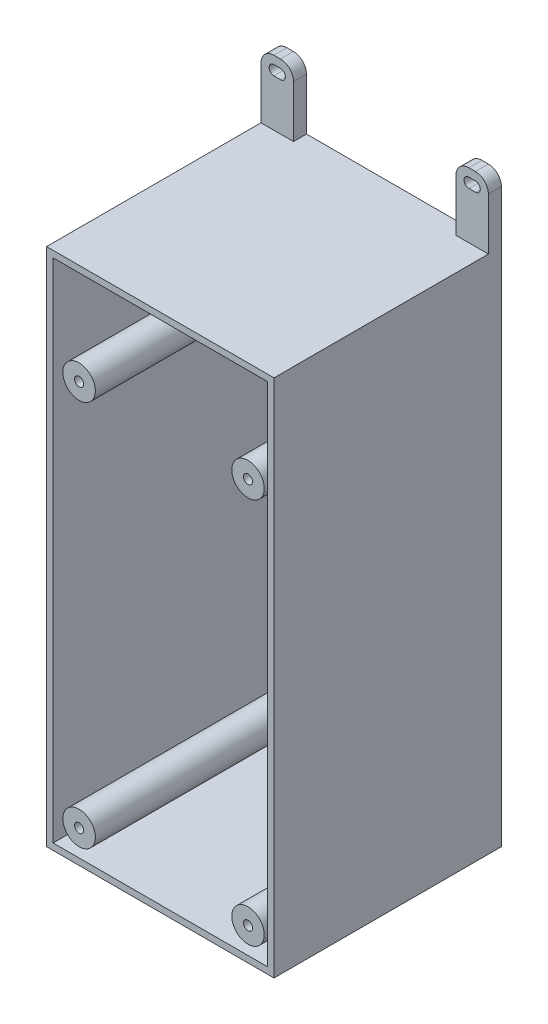
SolidWorks part; units mm, degrees
material "ABS"
ref_plane "Alzado" through (0, 0, 0) normal (0, 0, 1) x (1, 0, 0)
ref_plane "Planta" through (0, 0, 0) normal (0, 1, 0) x (1, 0, 0)
ref_plane "Vista lateral" through (0, 0, 0) normal (1, 0, 0) x (0, 0, -1)
sketch "Croquis1" plane through (0, 0, 0) normal (0, 0, 1) x (1, 0, 0)
  line L1 (0, 0) -> (70, 0)
  line L2 (0, 0) -> (0, 160)
  line L3 (0, 160) -> (70, 160)
  line L4 (70, 0) -> (70, 160)
  dimension "D1" = 70
  dimension "D2" = 160
extrude "Saliente-Extruir1" add sketch "Croquis1" along normal blind 70
shell "Vaciado1" thickness 2
sketch "Croquis2" plane through (0, 0, 2) normal (0, 0, 1) x (1, 0, 0)
  line L0 (68, 2) -> (68, 158) construction
  line L1 (53.5, 156.5) -> (66.5, 156.5)
  line L2 (53.5, 156.5) -> (53.5, 137.5)
  line L3 (53.5, 137.5) -> (66.5, 137.5)
  line L4 (66.5, 156.5) -> (66.5, 137.5)
  line L5 (68, 158) -> (2, 158) construction
  dimension "D1" = 13
  dimension "D2" = 19
  dimension "D3" = 1.5
  dimension "D4" = 1.5
extrude "Cortar-Extruir1" cut sketch "Croquis2" against normal through all
sketch "Croquis3" plane through (0, 0, 2) normal (0, 0, 1) x (1, 0, 0)
  line L0 (29.75, 10.8235) -> (40.25, 10.8235) construction
  line L1 (29.75, 14.5735) -> (40.25, 14.5735)
  line L2 (29.75, 7.0735) -> (40.25, 7.0735)
  line L3 (2, 2) -> (68, 2) construction
  line L4 (35, 2) -> (35, 29.5724) construction
  arc A0 (29.75, 14.5735) -> (29.75, 7.0735) centre (29.75, 10.8235) ccw
  arc A1 (40.25, 7.0735) -> (40.25, 14.5735) centre (40.25, 10.8235) ccw
  point P2 (35, 10.8235)
  point P7 (44, 10.8235)
  point P8 (26, 10.8235)
  dimension "D1" = 7.5
  dimension "D2" = 18
extrude "Cortar-Extruir2" cut sketch "Croquis3" against normal through all
sketch "Croquis4" plane through (2, 0, 0) normal (1, 0, 0) x (0, 0, -1)
  line L0 (-28, 145) -> (-20, 145) construction
  line L1 (-28, 148) -> (-20, 148)
  line L2 (-28, 142) -> (-20, 142)
  line L3 (-2, 158) -> (-2, 2) construction
  line L4 (-70, 158) -> (-2, 158) construction
  arc A0 (-28, 148) -> (-28, 142) centre (-28, 145) ccw
  arc A1 (-20, 142) -> (-20, 148) centre (-20, 145) ccw
  point P2 (-24, 145)
  point P7 (-17, 145)
  dimension "D1" = 11
  dimension "D2" = 6
  dimension "D3" = 15
  dimension "D4" = 10
extrude "Cortar-Extruir3" cut sketch "Croquis4" against normal through all
sketch "Croquis5" plane through (0, 0, 2) normal (0, 0, 1) x (1, 0, 0)
  line L0 (0, 0) -> (70, 0) construction
  line L1 (2, 158) -> (2, 2) construction
  line L2 (2, 2) -> (68, 2) construction
  line L3 (68, 2) -> (68, 158) construction
  line L4 (68, 158) -> (2, 158) construction
  circle A0 centre (9, 128) radius 5
  circle A1 centre (9, 9) radius 5
  circle A2 centre (61, 128) radius 5
  circle A3 centre (61, 9) radius 5
  circle A4 centre (61, 128) radius 3
  circle A5 centre (9, 128) radius 3
  circle A6 centre (9, 9) radius 3
  circle A7 centre (61, 9) radius 3
  dimension "D1" = 10
  dimension "D10" = 2
  dimension "D11" = 10
  dimension "D12" = 10
  dimension "D13" = 2
  dimension "D14" = 10
  dimension "D15" = 2
  dimension "D16" = 2
  dimension "D2" = 7
  dimension "D3" = 7
  dimension "D4" = 7
  dimension "D5" = 7
  dimension "D6" = 7
  dimension "D7" = 7
  dimension "D8" = 30
  dimension "D9" = 30
extrude "Saliente-Extruir2" add sketch "Croquis5" along normal blind 67
sketch "Croquis6" plane through (0, 0, 69) normal (0, 0, 1) x (1, 0, 0)
  circle A0 centre (9, 128) radius 1.4
  circle A1 centre (9, 128) radius 3.05
  circle A2 centre (61, 128) radius 1.4
  circle A3 centre (61, 128) radius 3.05
  circle A4 centre (61, 9) radius 1.4
  circle A5 centre (61, 9) radius 3.05
  circle A6 centre (9, 9) radius 1.4
  circle A7 centre (9, 9) radius 3.05
  dimension "D1" = 2.8
  dimension "D2" = 6.1
extrude "Saliente-Extruir3" add sketch "Croquis6" against normal blind 2
sketch "Croquis7" plane through (0, 0, 0) normal (0, 0, -1) x (-1, 0, 0)
  line L0 (-66, 176) -> (-64, 176) construction
  line L1 (-70, 160) -> (-60, 160)
  line L2 (-70, 160) -> (-70, 176)
  line L3 (-66, 180) -> (-64, 180)
  line L4 (-60, 160) -> (-60, 176)
  line L5 (0, 160) -> (-10, 160)
  line L6 (0, 160) -> (0, 176)
  line L7 (-4, 180) -> (-6, 180)
  line L8 (-10, 160) -> (-10, 176)
  line L9 (-66, 177.5) -> (-64, 177.5)
  line L10 (-66, 174.5) -> (-64, 174.5)
  line L11 (-6, 176) -> (-4, 176) construction
  line L12 (-6, 177.5) -> (-4, 177.5)
  line L13 (-6, 174.5) -> (-4, 174.5)
  arc A0 (0, 176) -> (-4, 180) centre (-4, 176) ccw
  arc A1 (-6, 180) -> (-10, 176) centre (-6, 176) ccw
  arc A2 (-64, 180) -> (-60, 176) centre (-64, 176) cw
  arc A3 (-70, 176) -> (-66, 180) centre (-66, 176) cw
  arc A4 (-66, 177.5) -> (-66, 174.5) centre (-66, 176) ccw
  arc A5 (-64, 174.5) -> (-64, 177.5) centre (-64, 176) ccw
  arc A6 (-6, 177.5) -> (-6, 174.5) centre (-6, 176) ccw
  arc A7 (-4, 174.5) -> (-4, 177.5) centre (-4, 176) ccw
  point P12 (0, 180)
  point P15 (-10, 180)
  point P18 (-60, 180)
  point P21 (-70, 180)
  point P22 (-65, 176)
  point P27 (-5, 176)
  dimension "D5" = 4
  dimension "D1" = 20
  dimension "D2" = 20
  dimension "D3" = 10
  dimension "D4" = 10
  dimension "D6" = 3
  dimension "D7" = 3
extrude "Saliente-Extruir4" add sketch "Croquis7" against normal blind 4
sketch "Croquis8" plane through (0, 0, 0) normal (0, 0, -1) x (-1, 0, 0)
  circle A0 centre (-61, 128) radius 4
  circle A1 centre (-9, 128) radius 4
  circle A2 centre (-61, 9) radius 4
  circle A3 centre (-9, 9) radius 4
extrude "Cortar-Extruir4" cut sketch "Croquis8" against normal blind 67
